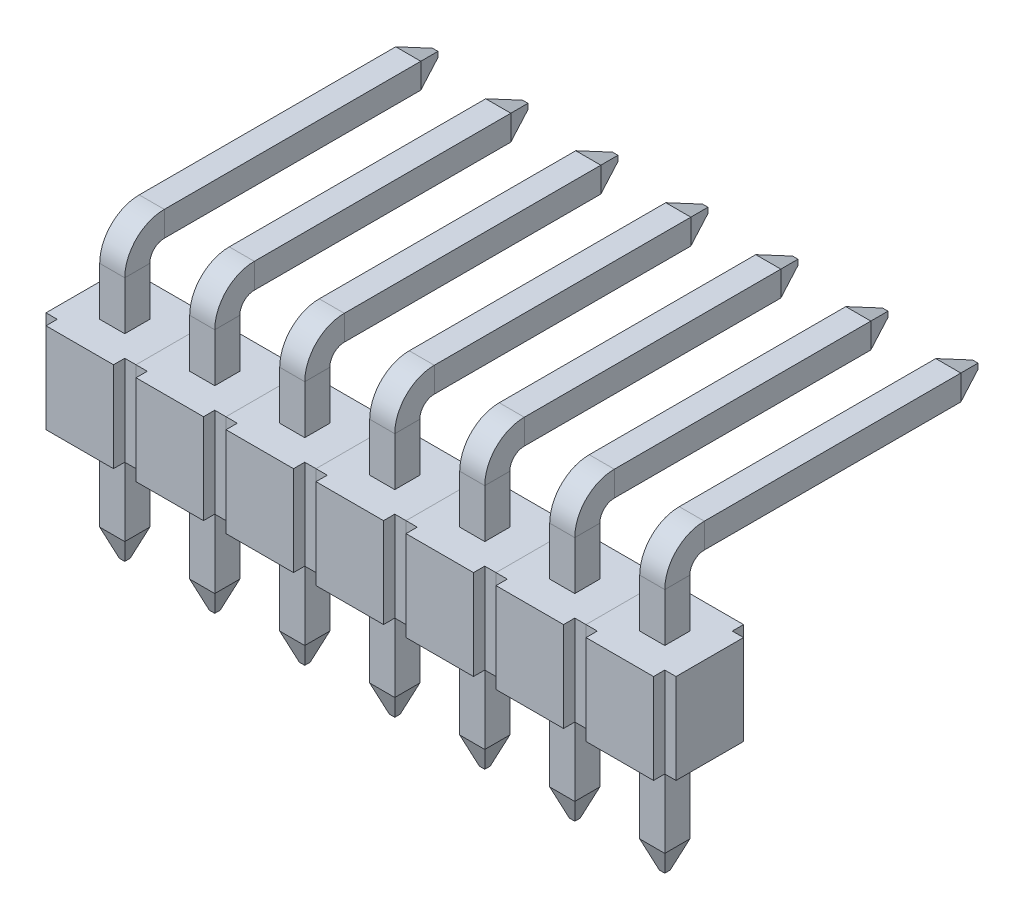
SolidWorks part; units mm, degrees
ref_plane "Front" through (0, 0, 0) normal (0, 0, 1) x (1, 0, 0)
ref_plane "Top" through (0, 0, 0) normal (0, 1, 0) x (1, 0, 0)
ref_plane "Right" through (0, 0, 0) normal (1, 0, 0) x (0, 0, -1)
sketch "Sketch1" plane through (0, 0, 0) normal (0, 1, 0) x (1, 0, 0)
  line L1 (1.27, -1.27) -> (-1.27, -1.27)
  line L2 (1.27, -1.27) -> (1.27, 1.27)
  line L3 (1.27, 1.27) -> (-1.27, 1.27)
  line L4 (-1.27, -1.27) -> (-1.27, 1.27)
  line L5 (1.27, -1.27) -> (-1.27, 1.27) construction
  line L6 (1.27, 1.27) -> (-1.27, -1.27) construction
  line L7 (1.27, 1.27) -> (0.9525, 1.27)
  line L8 (1.27, 1.27) -> (1.27, 0.9525)
  line L9 (1.27, 0.9525) -> (0.9525, 0.9525)
  line L10 (0.9525, 1.27) -> (0.9525, 0.9525)
  line L11 (1.27, -1.27) -> (0.9525, -1.27)
  line L12 (1.27, -1.27) -> (1.27, -0.9525)
  line L13 (1.27, -0.9525) -> (0.9525, -0.9525)
  line L14 (0.9525, -1.27) -> (0.9525, -0.9525)
  line L15 (-1.27, -1.27) -> (-0.9525, -1.27)
  line L16 (-1.27, -1.27) -> (-1.27, -0.9525)
  line L17 (-1.27, -0.9525) -> (-0.9525, -0.9525)
  line L18 (-0.9525, -1.27) -> (-0.9525, -0.9525)
  line L19 (-1.27, 1.27) -> (-0.9525, 1.27)
  line L20 (-1.27, 1.27) -> (-1.27, 0.9525)
  line L21 (-1.27, 0.9525) -> (-0.9525, 0.9525)
  line L22 (-0.9525, 1.27) -> (-0.9525, 0.9525)
  point P0 (0, 0)
  dimension "D1" = 2.54
  dimension "D2" = 1.905
extrude "Boss-Extrude1" add sketch "Sketch1" against normal mid plane 2.54 contours L3 L22 L21 L4 L17 L18 L1 L14 L13 L2 L9 L10
sketch "Sketch2" plane through (0, 0, 0) normal (0, 1, 0) x (1, 0, 0)
  line L1 (0.3536, -0.3536) -> (-0.3536, -0.3536)
  line L2 (0.3536, -0.3536) -> (0.3536, 0.3536)
  line L3 (0.3536, 0.3536) -> (-0.3536, 0.3536)
  line L4 (-0.3536, -0.3536) -> (-0.3536, 0.3536)
  line L5 (0.3536, -0.3536) -> (-0.3536, 0.3536) construction
  line L6 (0.3536, 0.3536) -> (-0.3536, -0.3536) construction
  point P0 (0, 0)
  dimension "D1" = 1
sketch "Sketch3" plane through (0, 0, 0) normal (1, 0, 0) x (0, 0, -1)
  line L0 (8.763, 3.399) -> (0.762, 3.399)
  line L1 (0, 2.637) -> (0, -4.572)
  line L2 (1.27, -1.27) -> (1.27, 1.27) construction
  line L3 (-0.9525, -1.27) -> (0.9525, -1.27) construction
  arc A0 (0.762, 3.399) -> (0, 2.637) centre (0.762, 2.637) ccw
  dimension "D3" = 0.762
  dimension "D1" = 7.493
  dimension "D2" = 3.302
  dimension "D4" = 4.669
sweep "Sweep1" add profiles "Sketch2" path "Sketch3"
chamfer "Chamfer1" distance 0.762 angle 20 8 edges at (0, -4.572, 0.3536) (0.3536, -4.572, 0) (0, -4.572, -0.3536) (-0.3536, -4.572, 0) (0, 3.0454, -8.763) (0.3536, 3.399, -8.763) (0, 3.7526, -8.763) (-0.3536, 3.399, -8.763)
pattern_linear "LPattern1" count 7 spacing 2.54 along (1, 0, 0) of bodies 116 104
